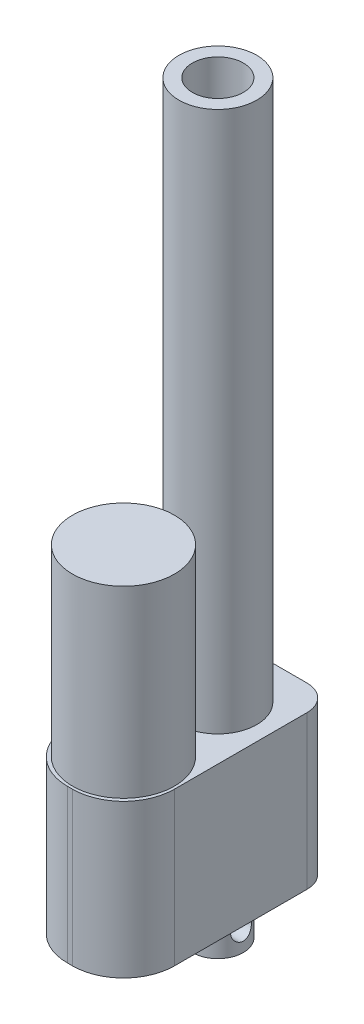
SolidWorks part; units mm, degrees
ref_plane "Front Plane" through (0, 0, 0) normal (0, 0, 1) x (1, 0, 0)
ref_plane "Top Plane" through (0, 0, 0) normal (0, 1, 0) x (1, 0, 0)
ref_plane "Right Plane" through (0, 0, 0) normal (1, 0, 0) x (0, 0, -1)
sketch "Sketch1" plane through (0, 0, 0) normal (0, 1, 0) x (1, 0, 0)
  circle A0 centre (0, 0) radius 15.25
extrude "Extrude1" add sketch "Sketch1" along normal blind 212
sketch "Sketch2" plane through (0, 0, 0) normal (0, -1, 0) x (1, 0, 0)
  line L0 (0, 24) -> (0, 36.1026) construction
  line L1 (-1, 58) -> (1, 58)
  line L2 (-21, 38) -> (-21, -24)
  line L3 (-21, -24) -> (21, -24)
  line L4 (21, 38) -> (21, -24)
  arc A0 (-1, 58) -> (-21, 38) centre (-1, 38) ccw
  arc A1 (21, 38) -> (1, 58) centre (1, 38) ccw
  point P0 (0, 0)
  dimension "D4" = 20
  dimension "D1" = 21
  dimension "D2" = 21
  dimension "D3" = 82
extrude "Extrude2" add sketch "Sketch2" along normal blind 60
sketch "Sketch3" plane through (0, 0, 0) normal (0, 1, 0) x (1, 0, 0)
  circle A0 centre (0, -37) radius 20
extrude "Extrude3" add sketch "Sketch3" along normal blind 72
sketch "Sketch4" plane through (0, -60, 0) normal (0, -1, 0) x (1, 0, 0)
  circle A0 centre (0, 0) radius 10
extrude "Extrude4" add sketch "Sketch4" along normal blind 20
sketch "Sketch5" plane through (0, 0, 0) normal (1, 0, 0) x (0, 0, -1)
  circle A0 centre (0, -72) radius 4.1
extrude "Extrude5" cut sketch "Sketch5" against normal mid plane 30
sketch "Sketch6" plane through (0, 212, 0) normal (0, 1, 0) x (1, 0, 0)
  circle A0 centre (0, 0) radius 10
extrude "Extrude6" cut sketch "Sketch6" against normal blind 150
fillet "Скругление1" radius 10 2 edges at (21, -30, -24) (-21, -30, -24)
